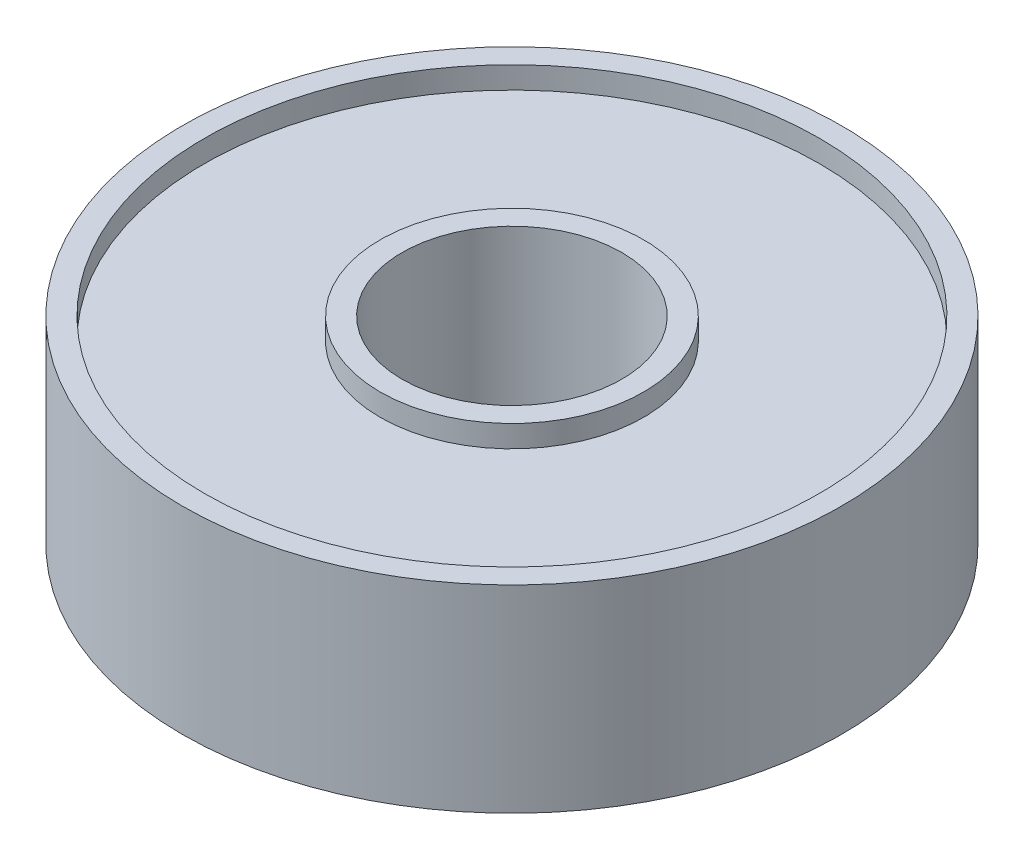
SolidWorks part; units mm, degrees
material "Chrome Stainless Steel"
ref_plane "Front Plane" through (0, 0, 0) normal (0, 0, 1) x (1, 0, 0)
ref_plane "Top Plane" through (0, 0, 0) normal (0, 1, 0) x (1, 0, 0)
ref_plane "Right Plane" through (0, 0, 0) normal (1, 0, 0) x (0, 0, -1)
sketch "Sketch1" plane through (0, 0, 0) normal (0, 1, 0) x (1, 0, 0)
  circle A0 centre (0, 0) radius 15
  dimension "D1" = 30
extrude "main extrusion" add sketch "Sketch1" along normal blind 9 contours A0
sketch "Sketch2" plane through (0, 9, 0) normal (0, 1, 0) x (1, 0, 0)
  circle A0 centre (0, 0) radius 5
  dimension "D1" = 10
extrude "ID bore" cut sketch "Sketch2" against normal blind 20
sketch "Sketch3" plane through (0, 9, 0) normal (0, 1, 0) x (1, 0, 0)
  circle A0 centre (0, 0) radius 14
  circle A1 centre (0, 0) radius 6
  dimension "D1" = 12
  dimension "D2" = 28
extrude "face recess" cut sketch "Sketch3" against normal blind 1
sketch "Sketch4" plane through (0, 0, 0) normal (0, -1, 0) x (1, 0, 0)
  circle A0 centre (0, 0) radius 14
  circle A1 centre (0, 0) radius 6
  dimension "D1" = 12
  dimension "D2" = 28
extrude "Cut-Extrude1" cut sketch "Sketch4" against normal blind 1
equation "\"D1@Sketch1\"=\"bearing OD\""
equation "\"D1@main extrusion\" = \"bearing depth\""
equation "\"D1@Sketch2\"=\"bearing ID\""
equation "\"motor mount pattern diameter\"= 30mm"
equation "\"D2@Sketch3\"=\"bearing OD\"-\"bearing outer race thickness\"*2"
equation "\"D1@Sketch3\"=\"bearing ID\"+\"bearing inner race thickness\"*2"
equation "\"D1@Sketch4\"=2*\"bearing inner race thickness\"+\"bearing ID\""
equation "\"D2@Sketch4\"=\"bearing OD\"-\"bearing outer race thickness\"*2"
equation "\"bearing OD\" = 30mm"
equation "\"bearing outer race thickness\"= 1mm"
equation "\"bearing ID\"= 10mm"
equation "\"bearing depth\"= 9mm"
equation "\"bearing inner race thickness\"= 1mm"
